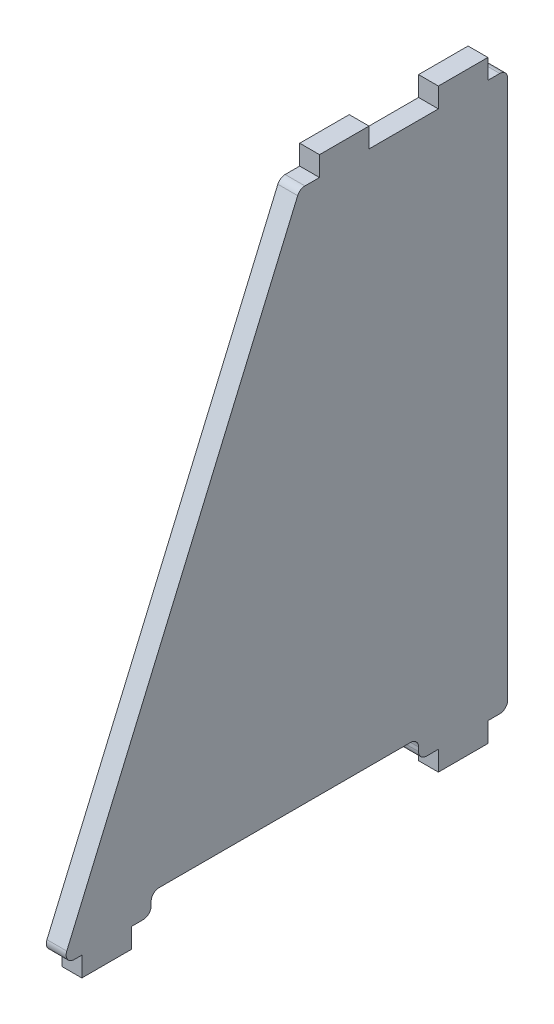
SolidWorks part; units mm, degrees
ref_plane "Front Plane" through (0, 0, 0) normal (0, 0, 1) x (1, 0, 0)
ref_plane "Top Plane" through (0, 0, 0) normal (0, 1, 0) x (1, 0, 0)
ref_plane "Right Plane" through (0, 0, 0) normal (1, 0, 0) x (0, 0, -1)
sketch "Sketch1" plane through (0, 0, 0) normal (1, 0, 0) x (0, 0, -1)
  line L0 (33.3375, 0) -> (-33.3375, 0) construction
  line L1 (-33.3375, 88.9) -> (33.3375, 88.9)
  line L2 (-33.3375, 88.9) -> (-33.3375, -88.9) construction
  line L3 (-33.3375, -88.9) -> (33.3375, -88.9)
  line L4 (33.3375, 88.9) -> (33.3375, -88.9)
  line L5 (26.9875, -88.9) -> (26.9875, -95.25)
  line L6 (-26.9875, 88.9) -> (-11.1125, 88.9)
  line L7 (-26.9875, 88.9) -> (-26.9875, 95.25)
  line L8 (-26.9875, 95.25) -> (-11.1125, 95.25)
  line L9 (-11.1125, 88.9) -> (-11.1125, 95.25)
  line L10 (11.1125, 88.9) -> (26.9875, 88.9)
  line L11 (11.1125, 88.9) -> (11.1125, 95.25)
  line L12 (11.1125, 95.25) -> (26.9875, 95.25)
  line L13 (26.9875, 88.9) -> (26.9875, 95.25)
  line L14 (11.1125, -95.25) -> (26.9875, -95.25)
  line L15 (11.1125, -88.9) -> (11.1125, -95.25)
  line L16 (-33.3375, -88.9) -> (-109.5375, -88.9)
  line L17 (-109.5375, -88.9) -> (-33.3375, 88.9)
  line L18 (-80.9625, -82.55) -> (4.7625, -82.55)
  line L19 (-103.1875, -88.9) -> (-87.3125, -88.9)
  line L20 (-103.1875, -88.9) -> (-103.1875, -95.25)
  line L21 (-103.1875, -95.25) -> (-87.3125, -95.25)
  line L22 (-87.3125, -88.9) -> (-87.3125, -95.25)
  line L23 (-80.9625, -82.55) -> (-80.9625, -88.9)
  line L24 (4.7625, -82.55) -> (4.7625, -88.9)
  point P4 (0, 88.9)
  point P6 (33.3375, 0)
  point P17 (11.1125, 92.075)
  point P29 (-87.3125, -92.075)
  dimension "D1" = 66.675
  dimension "D2" = 177.8
  dimension "D3" = 6.35
  dimension "D4" = 15.875
  dimension "D5" = 22.225
  dimension "D6" = 6.35
  dimension "D7" = 76.2
  dimension "D8" = 114.3
  dimension "D9" = 6.35
  dimension "D10" = 85.725
  dimension "D11" = 6.35
extrude "Boss-Extrude1" add sketch "Sketch1" along normal blind 6.35 contours L18 L24 L3 L4 L1 L17 L16 L23 | L3 L15 L14 L5 | L1 L9 L8 L7 | L1 L13 L12 L11 | L20 L19 L22 L21
fillet "Fillet1" radius 2.54 8 edges at (3.175, 88.9, 33.3375) (3.175, 88.9, -33.3375) (3.175, -88.9, -33.3375) (3.175, -88.9, 109.5375) (3.175, -88.9, -4.7625) (3.175, -82.55, -4.7625) (3.175, -82.55, 80.9625) (3.175, -88.9, 80.9625)
